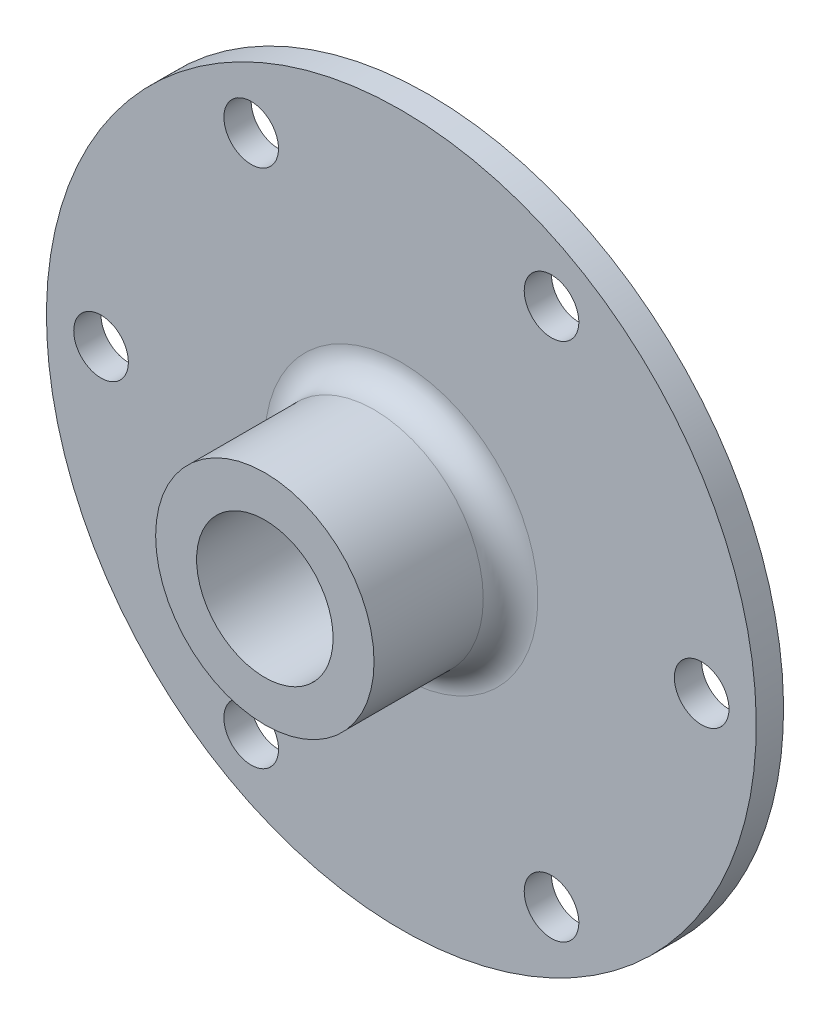
SolidWorks part; units mm, degrees
material "AISI 1020"
ref_plane "Front Plane" through (0, 0, 0) normal (0, 0, 1) x (1, 0, 0)
ref_plane "Top Plane" through (0, 0, 0) normal (0, 1, 0) x (1, 0, 0)
ref_plane "Right Plane" through (0, 0, 0) normal (1, 0, 0) x (0, 0, -1)
sketch "Sketch1" plane through (0, 0, 0) normal (1, 0, 0) x (0, 0, -1)
  line L2 (0, 0) -> (0, 41.275)
  line L3 (0, 41.275) -> (-3.175, 41.275)
  line L4 (-3.175, 12.7) -> (-3.175, 41.275)
  line L5 (0, 0) -> (-19.05, 0)
  line L7 (-3.175, 12.7) -> (-19.05, 12.7)
  line L8 (-19.05, 0) -> (-19.05, 12.7)
  dimension "D1" = 3.175
  dimension "D2" = 41.275
  dimension "D3" = 19.05
  dimension "D4" = 12.7
revolve "Revolve" add sketch "Sketch1" angle 360 about L5
sketch "Sketch2" plane through (0, 0, 19.05) normal (0, 0, 1) x (1, 0, 0)
  circle A0 centre (0, 0) radius 7.9375
extrude "Center Cut" cut sketch "Sketch2" against normal through all
sketch "Sketch3" plane through (0, 0, 3.175) normal (0, 0, 1) x (1, 0, 0)
  line L0 (0, 0) -> (34.925, 0) construction
  circle A0 centre (34.925, 0) radius 3.175
extrude "Peripheral Cut" cut sketch "Sketch3" against normal through all
pattern_circular "CirPattern" count 6 over 360 about axis through (0, 0, 0) along (0, 0, 1) of "Peripheral Cut"
fillet "Fillet" radius 3.175 1 edges at (0, 12.7, 3.175)
